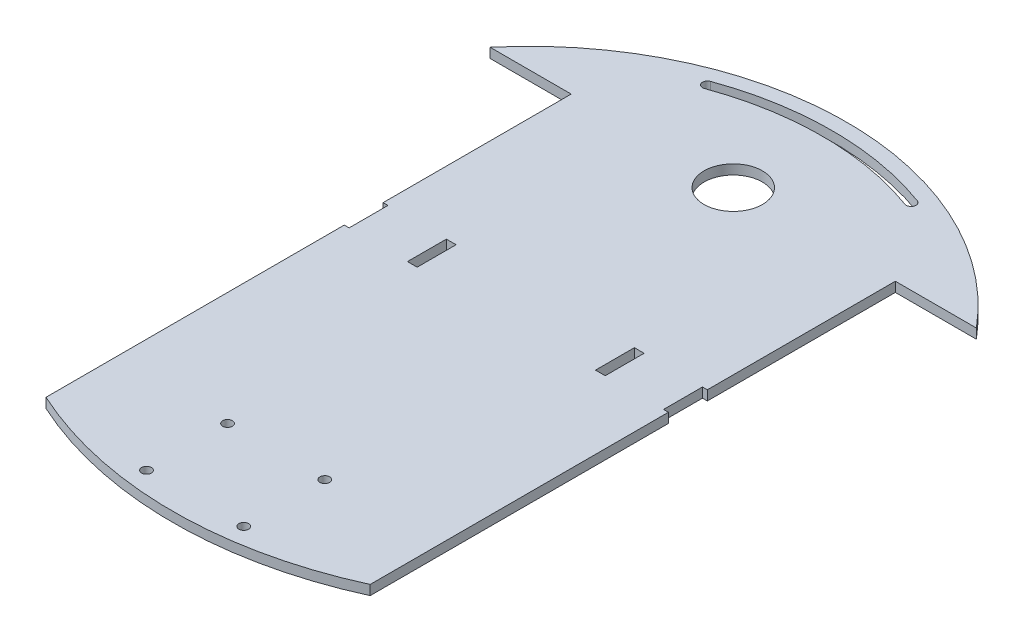
SolidWorks part; units mm, degrees
ref_plane "Front Plane" through (0, 0, 0) normal (0, 0, 1) x (1, 0, 0)
ref_plane "Top Plane" through (0, 0, 0) normal (0, 1, 0) x (1, 0, 0)
ref_plane "Right Plane" through (0, 0, 0) normal (1, 0, 0) x (0, 0, -1)
sketch "Sketch1" plane through (0, 0, 0) normal (0, 1, 0) x (1, 0, 0)
  line L14 (50, -81) -> (50, 11)
  line L15 (50, 81) -> (75, 81)
  line L16 (0, -55) -> (0, 55) construction
  line L17 (-55, 0) -> (55, 0) construction
  line L18 (50, 23) -> (48.5, 23)
  line L19 (48.5, 23) -> (48.5, 11)
  line L20 (48.5, 11) -> (50, 11)
  line L21 (50, 23) -> (50, 81)
  line L22 (-27.5, 11) -> (-27.5, 23)
  line L23 (30.5, 11) -> (27.5, 11)
  line L24 (30.5, 11) -> (30.5, 23)
  line L25 (30.5, 23) -> (27.5, 23)
  line L26 (27.5, 11) -> (27.5, 23)
  line L27 (-30.5, 23) -> (-27.5, 23)
  line L28 (-30.5, 11) -> (-30.5, 23)
  line L29 (-30.5, 11) -> (-27.5, 11)
  line L30 (-50, 23) -> (-50, 81)
  line L31 (-48.5, 11) -> (-50, 11)
  line L32 (-48.5, 23) -> (-48.5, 11)
  line L33 (-50, 23) -> (-48.5, 23)
  line L34 (-50, 81) -> (-75, 81)
  line L35 (-50, -81) -> (-50, 11)
  arc A11 (-75, 81) -> (75, 81) centre (0, 18.1429) cw
  arc A12 (-50, -81) -> (50, -81) centre (0, 28.0871) ccw
  circle A13 centre (0, 81) radius 9
  arc A14 (-31.417, 104.4603) -> (31.417, 104.4603) centre (0, 18.1429) cw construction
  arc A15 (31.93, 105.8699) -> (-31.93, 105.8699) centre (0, 18.1429) ccw
  arc A16 (30.904, 103.0508) -> (-30.904, 103.0508) centre (0, 18.1429) ccw
  arc A17 (30.904, 103.0508) -> (31.93, 105.8699) centre (31.417, 104.4603) ccw
  arc A18 (-31.93, 105.8699) -> (-30.904, 103.0508) centre (-31.417, 104.4603) ccw
  point P2 (0, 0)
  point P10 (62.5, 81)
  point P13 (49.25, 23)
  point P18 (0, 0)
  point P19 (0, 0)
  point P20 (0, 0)
  point P38 (0, 116)
  point P44 (0, 110)
  dimension "D1" = 50
  dimension "D2" = 81
  dimension "D5" = 58
  dimension "D6" = 12
  dimension "D7" = 1.5
  dimension "D9" = 12
  dimension "D4" = 81
  dimension "D11" = 120
  dimension "D16" = 35
  dimension "D17" = 3
  dimension "D18" = 6
  dimension "D3" = 25
  dimension "D8" = 18
  dimension "D10" = 3
  dimension "D19" = 0
  dimension "D20" = 40
extrude "Boss-Extrude1" add sketch "Sketch1" along normal blind 3
sketch "Sketch2" plane through (0, 3, 0) normal (0, 1, 0) x (1, 0, 0)
  line L0 (-1.65, 0) -> (1.65, 0) construction
  line L1 (0, -1.65) -> (0, 1.65) construction
  circle A0 centre (15, -60) radius 1.5
  circle A1 centre (15, -85) radius 1.5
  circle A2 centre (-15, -85) radius 1.5
  circle A3 centre (-15, -60) radius 1.5
  dimension "D1" = 60
  dimension "D3" = 25
  dimension "D2" = 15
extrude "Cut-Extrude1" cut sketch "Sketch2" against normal through all
